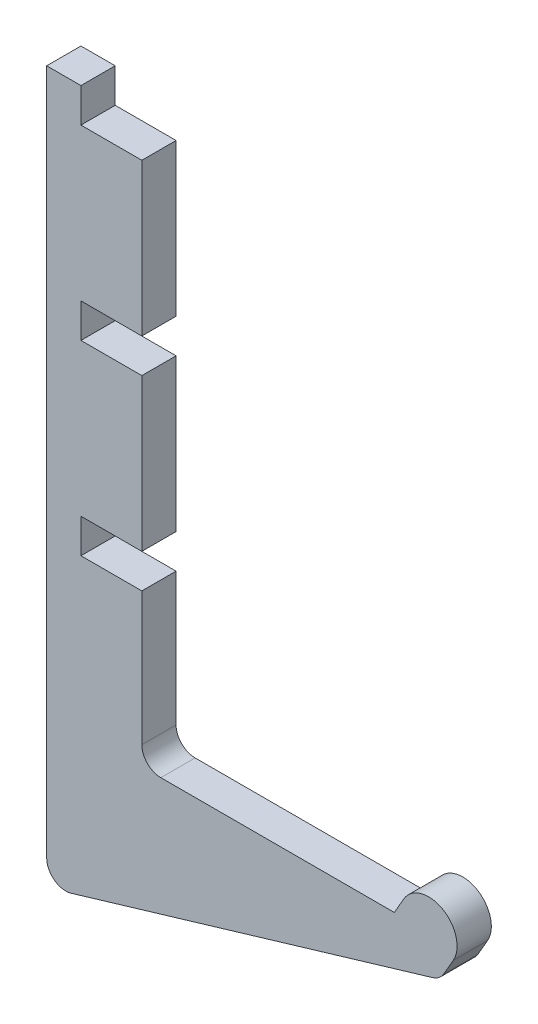
SolidWorks part; units mm, degrees
ref_plane "Plan de face" through (0, 0, 0) normal (0, 0, 1) x (1, 0, 0)
ref_plane "Plan de dessus" through (0, 0, 0) normal (0, 1, 0) x (1, 0, 0)
ref_plane "Plan de droite" through (0, 0, 0) normal (1, 0, 0) x (0, 0, -1)
sketch "Esquisse1" plane through (0, 0, 0) normal (0, 0, 1) x (1, 0, 0)
  line L0 (0, 614) -> (0, 253.4124)
  line L3 (12.8544, 243.8284) -> (202.8544, 300.416)
  line L4 (200, 320) -> (60, 320)
  line L5 (50, 330) -> (50, 614)
  line L6 (50, 614) -> (0, 614)
  arc A0 (202.8544, 300.416) -> (200, 320) centre (200, 310) ccw
  arc A1 (60, 320) -> (50, 330) centre (60, 330) cw
  arc A2 (0, 253.4124) -> (12.8544, 243.8284) centre (10, 253.4124) ccw
  point P11 (0, 240)
  dimension "D3" = 10
  dimension "D5" = 10
  dimension "D1" = 50
  dimension "D2" = 80
  dimension "D4" = 150
extrude "Boss.-Extru.1" add sketch "Esquisse1" along normal blind 18
sketch "Esquisse2" plane through (0, 0, 18) normal (0, 0, 1) x (1, 0, 0)
  line L0 (50, 330) -> (50, 614) construction
  line L1 (18, 596) -> (50, 596)
  line L2 (18, 596) -> (18, 614)
  line L3 (18, 614) -> (50, 614)
  line L4 (50, 596) -> (50, 614)
  line L5 (50, 516) -> (18, 516)
  line L6 (50, 516) -> (50, 498)
  line L7 (50, 498) -> (18, 498)
  line L8 (18, 516) -> (18, 498)
  line L11 (50, 418) -> (18, 418)
  line L12 (50, 418) -> (50, 400)
  line L13 (50, 400) -> (18, 400)
  line L14 (18, 418) -> (18, 400)
  line L15 (48, 516) -> (120, 516) construction
  line L16 (48, 418) -> (120, 418) construction
extrude "Enlèv. mat.-Extru.1" cut sketch "Esquisse2" against normal through all
sketch "Esquisse3" plane through (0, 0, 18) normal (0, 0, 1) x (1, 0, 0)
  line L0 (208.6603, 305) -> (213.6603, 313.6603)
  line L1 (213.6603, 313.6603) -> (187.6795, 328.6603) construction
  line L2 (187.6795, 328.6603) -> (182.6795, 320)
  line L3 (200, 320) -> (60, 320) construction
  line L4 (182.6795, 320) -> (208.6603, 305)
  arc A1 (202.8544, 300.416) -> (200, 320) centre (200, 310) ccw construction
  arc A2 (187.6795, 328.6603) -> (213.6603, 313.6603) centre (200.6699, 321.1603) cw
  dimension "D1" = 15
  dimension "D2" = 10
extrude "Boss.-Extru.2" add sketch "Esquisse3" against normal blind 18
